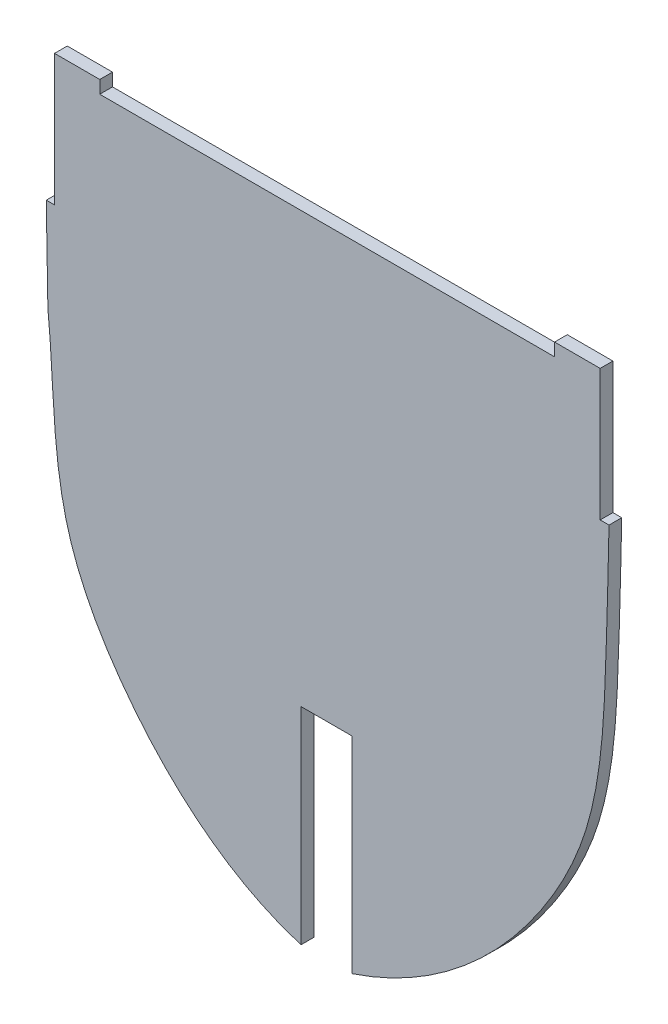
SolidWorks part; units mm, degrees
ref_plane "前视基准面" through (0, 0, 0) normal (0, 0, 1) x (1, 0, 0)
ref_plane "上视基准面" through (0, 0, 0) normal (0, 1, 0) x (1, 0, 0)
ref_plane "右视基准面" through (0, 0, 0) normal (1, 0, 0) x (0, 0, -1)
other "Configuration Table"
sketch "草图1" plane through (0, 0, 0) normal (0, 0, 1) x (1, 0, 0)
  line L0 (376.6667, 613.5) -> (1883.3333, 613.5) construction
  line L4 (244.9678, 542.3934) -> (173.5311, 542.3934)
  line L5 (252.1323, 544.4045) -> (244.9678, 544.4045)
  line L6 (244.9678, 544.4045) -> (244.9678, 542.3934)
  line L7 (173.5311, 544.4045) -> (166.4272, 544.4045)
  line L8 (166.4272, 544.4045) -> (166.4272, 523.7846)
  line L9 (166.4272, 523.7846) -> (165.1253, 523.7846)
  line L10 (173.5311, 542.3934) -> (173.5311, 544.4045)
  line L11 (252.1323, 544.4045) -> (252.1323, 523.7846)
  line L12 (252.1323, 523.7846) -> (253.522, 523.7846)
  line L19 (205.161, 472.9051) -> (205.161, 442.5143)
  line L21 (213.1633, 472.9051) -> (213.1633, 442.5774)
  line L23 (205.161, 472.9051) -> (205.161, 474.9051)
  line L24 (205.161, 474.9051) -> (213.1633, 474.9051)
  line L25 (213.1633, 474.9051) -> (213.1633, 472.9051)
  spline S0 degree 3 poles (253.522, 523.7846) (253.3889, 517.5658) (253.0321, 502.9635) (252.104, 483.2246) (243.3318, 465.6108) (231.6123, 451.7089) (219.9616, 444.8239) (213.1633, 442.5774) knots 0 0 0 0 0.186774 0.443708 0.581361 0.772361 0.983205 0.983205 0.983205 0.983205
  spline S1 degree 1 poles (165.1253, 523.7846) (165.3815, 509.1617) knots 0 0 1 1
  spline S2 degree 3 poles (165.3815, 509.1617) (166.3985, 499.5814) (165.6607, 482.5966) (178.5752, 459.9186) (192.3118, 447.2569) (203.1459, 443.1113) (205.161, 442.5143) knots 0 0 0 0 0.348659 0.570108 0.906139 0.98014 0.98014 0.98014 0.98014
  dimension "D1" = 30.3277
  dimension "D2" = 8.0023
extrude "凸台-拉伸1" add sketch "草图1" along normal blind 2
